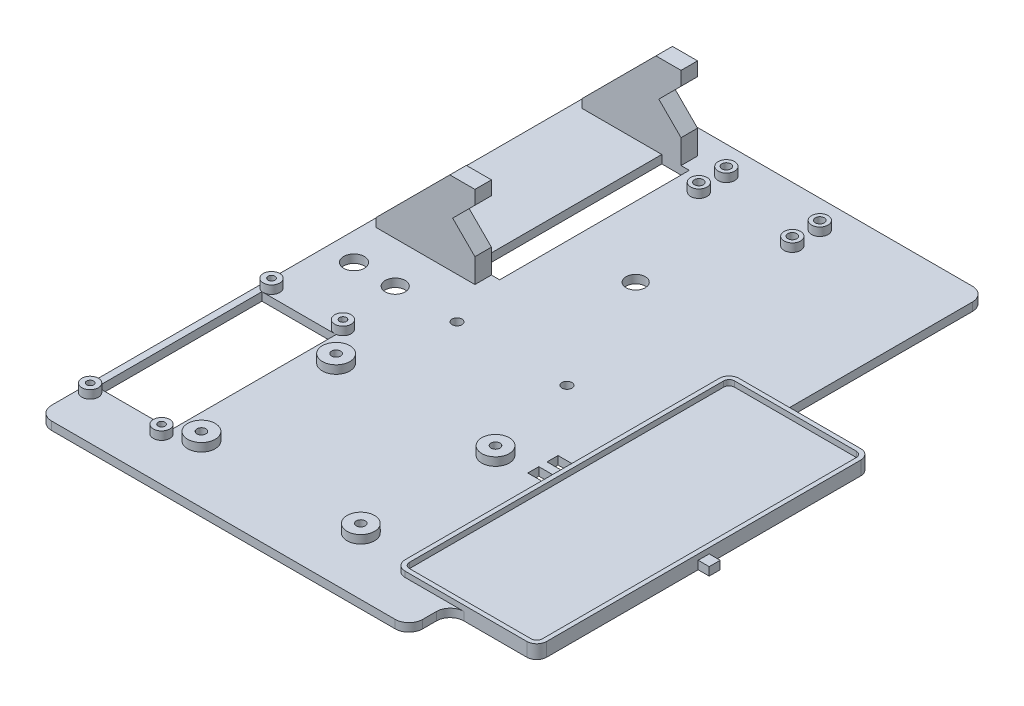
SolidWorks part; units mm, degrees
material "ABS"
ref_plane "Front" through (0, 0, 0) normal (0, 0, 1) x (1, 0, 0)
ref_plane "Top" through (0, 0, 0) normal (0, 1, 0) x (1, 0, 0)
ref_plane "Right" through (0, 0, 0) normal (1, 0, 0) x (0, 0, -1)
sketch "Sketch1" plane through (0, 0, 0) normal (0, 1, 0) x (1, 0, 0)
  line L1 (-67.5, -105) -> (67.5, -105)
  line L2 (-67.5, -105) -> (-67.5, 105)
  line L3 (-67.5, 105) -> (67.5, 105)
  line L4 (67.5, -105) -> (67.5, 105)
  line L5 (-67.5, -105) -> (67.5, 105) construction
  line L6 (-67.5, 105) -> (67.5, -105) construction
  point P0 (0, 0)
  dimension "D1" = 210
  dimension "D2" = 135
extrude "Boss-Extrude1" add sketch "Sketch1" along normal blind 3
sketch "Sketch2" plane through (0, 3, 0) normal (0, 1, 0) x (1, 0, 0)
  line L0 (-17, 95) -> (17, 95) construction
  line L1 (17, 95) -> (17, 85) construction
  line L2 (17, 85) -> (-17, 85) construction
  line L3 (-17, 85) -> (-17, 95) construction
  line L4 (67.5, 105) -> (-67.5, 105) construction
  line L5 (-29, -35) -> (29, -35) construction
  line L6 (29, -35) -> (29, -84) construction
  line L7 (29, -84) -> (-29, -84) construction
  line L8 (-29, -84) -> (-29, -35) construction
  circle A0 centre (-17, 95) radius 3
  circle A1 centre (17, 95) radius 3
  circle A2 centre (-17, 85) radius 3
  circle A3 centre (17, 85) radius 3
  circle A4 centre (-29, -35) radius 5
  circle A5 centre (29, -35) radius 5
  circle A6 centre (29, -84) radius 5
  circle A7 centre (-29, -84) radius 5
  point P8 (0, 95)
  point P11 (0, 105)
  point P20 (0, -35)
  point P21 (0, 85)
  dimension "D3" = 6
  dimension "D5" = 10
  dimension "D1" = 10
  dimension "D2" = 34
  dimension "D4" = 10
  dimension "D6" = 120
  dimension "D7" = 58
  dimension "D8" = 49
extrude "Boss-Extrude2" add sketch "Sketch2" along normal blind 3
sketch "Sketch3" plane through (0, 3, 0) normal (0, 1, 0) x (1, 0, 0)
  line L1 (-38.5, -23) -> (-64.5, -23) construction
  line L2 (-38.5, -23) -> (-38.5, -89) construction
  line L3 (-38.5, -89) -> (-64.5, -89) construction
  line L4 (-64.5, -23) -> (-64.5, -89) construction
  line L5 (-67.5, 105) -> (-67.5, -105) construction
  line L6 (-67.5, -105) -> (67.5, -105) construction
  circle A0 centre (-64.5, -23) radius 3
  circle A1 centre (-38.5, -23) radius 3
  circle A2 centre (-38.5, -89) radius 3
  circle A3 centre (-64.5, -89) radius 3
  dimension "D1" = 6
  dimension "D2" = 66
  dimension "D3" = 26
  dimension "D4" = 16
  dimension "D5" = 3
extrude "Boss-Extrude3" add sketch "Sketch3" along normal blind 3
sketch "Sketch4" plane through (0, 0, 0) normal (0, -1, 0) x (1, 0, 0)
  line L0 (-67.5, 105) -> (67.5, 105) construction
  line L1 (47.5, -31.5) -> (99, -31.5)
  line L2 (47.5, -31.5) -> (47.5, 90)
  line L3 (47.5, 90) -> (99, 90)
  line L4 (99, -31.5) -> (99, 90)
  line L5 (67.5, 105) -> (67.5, -105) construction
  dimension "D1" = 51.5
  dimension "D2" = 121.5
  dimension "D3" = 15
  dimension "D4" = 20
extrude "Boss-Extrude4" add sketch "Sketch4" against normal blind 5
sketch "Sketch5" plane through (0, 5, 0) normal (0, 1, 0) x (1, 0, 0)
  line L0 (97.4, 29.9) -> (49.1, 29.9)
  line L1 (49.1, 29.9) -> (49.1, -88.4)
  line L2 (49.1, -88.4) -> (97.4, -88.4)
  line L3 (97.4, -88.4) -> (97.4, 29.9)
  line L4 (47.5, 31.5) -> (47.5, -90)
  line L5 (47.5, -90) -> (99, -90)
  line L6 (99, -90) -> (99, 31.5)
  line L7 (99, 31.5) -> (47.5, 31.5)
  line L8 (47.5, 31.5) -> (47.5, -90) construction
  line L9 (47.5, -90) -> (99, -90) construction
  line L10 (99, -90) -> (99, 31.5) construction
  line L11 (99, 31.5) -> (47.5, 31.5) construction
  dimension "D1" = 0
  dimension "D2" = 1.6
extrude "Cut-Extrude1" cut sketch "Sketch5" against normal up to surface (2 mm away) contours L1 L2 L3 L0 up to face at (-38.5, 3, 86)
fillet "Fillet1" radius 2 4 edges at (49.1, 4, 88.4) (49.1, 4, -29.9) (97.4, 4, -29.9) (97.4, 4, 88.4)
fillet "Fillet2" radius 3.6 4 edges at (47.5, 4, 90) (47.5, 4, -31.5) (99, 2.5, -31.5) (99, 2.5, 90)
fillet "Fillet3" radius 5 5 edges at (67.5, 1.5, -105) (-67.5, 1.5, -105) (-67.5, 1.5, 105) (67.5, 1.5, 105) (67.5, 1.5, 90)
sketch "Sketch6" plane through (0, 3, 0) normal (0, 1, 0) x (1, 0, 0)
  line L0 (0, 0) -> (0, 45) construction
  circle A0 centre (0, 45) radius 3.5
  dimension "D1" = 7
  dimension "D2" = 45
extrude "Cut-Extrude2" cut sketch "Sketch6" against normal blind 5
sketch "Sketch7" plane through (0, 3, 0) normal (0, 1, 0) x (1, 0, 0)
  line L1 (-28.494, 96.0069) -> (-64.494, 96.0069)
  line L2 (-28.494, 96.0069) -> (-28.494, 90.0069)
  line L3 (-28.494, 90.0069) -> (-64.494, 90.0069)
  line L4 (-64.494, 96.0069) -> (-64.494, 90.0069)
  line L5 (-28.494, 21.0069) -> (-64.494, 21.0069)
  line L6 (-28.494, 21.0069) -> (-28.494, 15.0069)
  line L7 (-28.494, 15.0069) -> (-64.494, 15.0069)
  line L8 (-64.494, 21.0069) -> (-64.494, 15.0069)
  point P8 (-28.494, 93.0069)
  point P9 (-28.494, 18.0069)
  dimension "D1" = 75
  dimension "D2" = 36
  dimension "D3" = 6
extrude "Boss-Extrude5" add sketch "Sketch7" along normal blind 30
sketch "Sketch8" plane through (0, 0, -96.0069) normal (0, 0, -1) x (-1, 0, 0)
  line L0 (64.494, 33) -> (64.494, 6.1299)
  line L1 (64.494, 33) -> (64.494, 3) construction
  line L2 (64.494, 6.1299) -> (37.624, 33)
  line L3 (28.494, 33) -> (64.494, 33) construction
  line L4 (37.624, 33) -> (64.494, 33)
  dimension "D1" = 38
  dimension "D2" = 45
extrude "Cut-Extrude3" cut sketch "Sketch8" against normal up to surface (81 mm away) up to face at (-46.494, 18, -15.0069)
sketch "Sketch9" plane through (-35.312, 35.312, 0) normal (-0.7071, 0.7071, 0) x (0, 0, 1)
  line L0 (-15.0069, -3.2696) -> (-21.0069, -3.2696) construction
  line L1 (-96.0069, -3.2696) -> (-90.0069, -3.2696) construction
  circle A0 centre (-18.0069, -5.2696) radius 1.625
  circle A1 centre (-93.0069, -5.2696) radius 1.625
  point P4 (0, 0)
  point P7 (-18.0069, -3.2696)
  point P8 (0, 0)
  point P11 (-93.0069, -3.2696)
  point P12 (0, 0)
  point P13 (-18.0069, -5.2696)
  dimension "D2" = 3.25
  dimension "D1" = 2
extrude "Cut-Extrude4" cut sketch "Sketch9" against normal up to surface (16.5367 mm away)
sketch "Sketch10" plane through (0, 3, 0) normal (0, 1, 0) x (1, 0, 0)
  line L0 (-64.5, -23) -> (-38.5, -89) construction
  line L1 (-65, -26) -> (-38, -26)
  line L2 (-65, -26) -> (-65, -86)
  line L3 (-65, -86) -> (-38, -86)
  line L4 (-38, -26) -> (-38, -86)
  line L5 (-64.494, 15.0069) -> (-28.494, 15.0069) construction
  line L6 (-67.5, 100) -> (-67.5, -23) construction
  circle A0 centre (-42.5, 0.0069) radius 3.625
  circle A1 centre (-57.5, 0.0069) radius 3.75
  point P8 (-38, -56)
  point P13 (-51.5, -56)
  point P14 (-51.5, -26)
  dimension "D3" = 7.25
  dimension "D4" = 7.5
  dimension "D1" = 60
  dimension "D2" = 27
  dimension "D5" = 15
  dimension "D6" = 10
  dimension "D7" = 15
extrude "Cut-Extrude5" cut sketch "Sketch10" against normal through all
sketch "Sketch11" plane through (0, 3, 0) normal (0, 1, 0) x (1, 0, 0)
  line L0 (45.5, -27.75) -> (45.5, -30.75) construction
  line L1 (45.5, -23.75) -> (40.5, -23.75)
  line L2 (45.5, -23.75) -> (45.5, -27.75)
  line L3 (45.5, -27.75) -> (40.5, -27.75)
  line L4 (40.5, -23.75) -> (40.5, -27.75)
  line L5 (45.5, -30.75) -> (40.5, -30.75)
  line L6 (45.5, -30.75) -> (45.5, -34.75)
  line L7 (45.5, -34.75) -> (40.5, -34.75)
  line L8 (40.5, -30.75) -> (40.5, -34.75)
  line L9 (47.5, -86.4) -> (47.5, 27.9) construction
  point P8 (45.5, -29.25)
  point P11 (47.5, -29.25)
  dimension "D1" = 2
  dimension "D2" = 3
  dimension "D3" = 5
  dimension "D4" = 4
extrude "Cut-Extrude6" cut sketch "Sketch11" against normal through all
sketch "Sketch12" plane through (0, 0, 0) normal (0, -1, 0) x (1, 0, 0)
  line L0 (99, -27.9) -> (99, 86.4) construction
  line L1 (99, 27.25) -> (103, 27.25)
  line L2 (99, 27.25) -> (99, 31.25)
  line L3 (99, 31.25) -> (103, 31.25)
  line L4 (103, 27.25) -> (103, 31.25)
  point P6 (99, 29.25)
  point P7 (99, 29.25)
  dimension "D1" = 4
  dimension "D2" = 4
extrude "Boss-Extrude6" add sketch "Sketch12" against normal blind 3
sketch "Sketch13" plane through (0, 3, 0) normal (0, 1, 0) x (1, 0, 0)
  line L0 (-28.494, 21.0069) -> (-64.494, 21.0069) construction
  line L1 (-25.494, 21.0069) -> (-35.494, 21.0069)
  line L2 (-25.494, 21.0069) -> (-25.494, 90.0069)
  line L3 (-25.494, 90.0069) -> (-35.494, 90.0069)
  line L4 (-35.494, 21.0069) -> (-35.494, 90.0069)
  line L5 (-64.494, 90.0069) -> (-28.494, 90.0069) construction
  line L6 (-28.494, 90.0069) -> (-28.494, 96.0069) construction
  dimension "D1" = 3
  dimension "D2" = 10
extrude "Cut-Extrude7" cut sketch "Sketch13" against normal through all
sketch "Sketch14" plane through (0, 6, 0) normal (0, 1, 0) x (1, 0, 0)
  circle A0 centre (-38.5, -89) radius 1.25
  circle A1 centre (-64.5, -89) radius 1.25
  circle A2 centre (-38.5, -23) radius 1.25
  circle A3 centre (-64.5, -23) radius 1.25
  circle A4 centre (-29, -35) radius 1.625
  circle A5 centre (-29, -84) radius 1.625
  circle A6 centre (29, -84) radius 1.625
  circle A7 centre (29, -35) radius 1.625
  circle A8 centre (17, 95) radius 1.625
  circle A9 centre (17, 85) radius 1.625
  circle A10 centre (-17, 85) radius 1.625
  circle A11 centre (-17, 95) radius 1.625
  dimension "D1" = 2.5
  dimension "D2" = 3.25
  dimension "D3" = 3.25
extrude "Cut-Extrude8" cut sketch "Sketch14" against normal through all
sketch "Sketch15" plane through (-35.312, 35.312, 0) normal (-0.7071, 0.7071, 0) x (0, 0, 1)
  line L0 (-96.0069, -3.2696) -> (-96.0069, -41.2696) construction
  line L1 (-96.0069, -11.8138) -> (-90.0069, -11.8138)
  line L2 (-96.0069, -11.8138) -> (-96.0069, 3.1862)
  line L3 (-96.0069, 3.1862) -> (-90.0069, 3.1862)
  line L4 (-90.0069, -11.8138) -> (-90.0069, 3.1862)
  line L5 (-21.0069, -41.2696) -> (-21.0069, -3.2696) construction
  line L6 (-21.0069, -11.8138) -> (-15.0069, -11.8138)
  line L7 (-21.0069, -11.8138) -> (-21.0069, 3.1862)
  line L8 (-21.0069, 3.1862) -> (-15.0069, 3.1862)
  line L9 (-15.0069, -11.8138) -> (-15.0069, 3.1862)
  line L10 (-90.0069, 3.1862) -> (-96.0069, 3.1862) construction
  line L12 (-90.0069, -3.2696) -> (-90.0069, -41.2696) construction
  point P16 (0, 0)
  dimension "D1" = 15
extrude "Cut-Extrude9" cut sketch "Sketch15" against normal up to surface (11.4558 mm away) from offset 10 offset against normal yes
sketch "Sketch16" plane through (0, 3, 0) normal (0, 1, 0) x (1, 0, 0)
  line L0 (20, 0) -> (-20, 0) construction
  circle A0 centre (20, 0) radius 1.8
  circle A1 centre (-20, 0) radius 1.8
  point P2 (0, 0)
  dimension "D1" = 3.6
  dimension "D2" = 40
extrude "Cut-Extrude10" cut sketch "Sketch16" against normal through all
